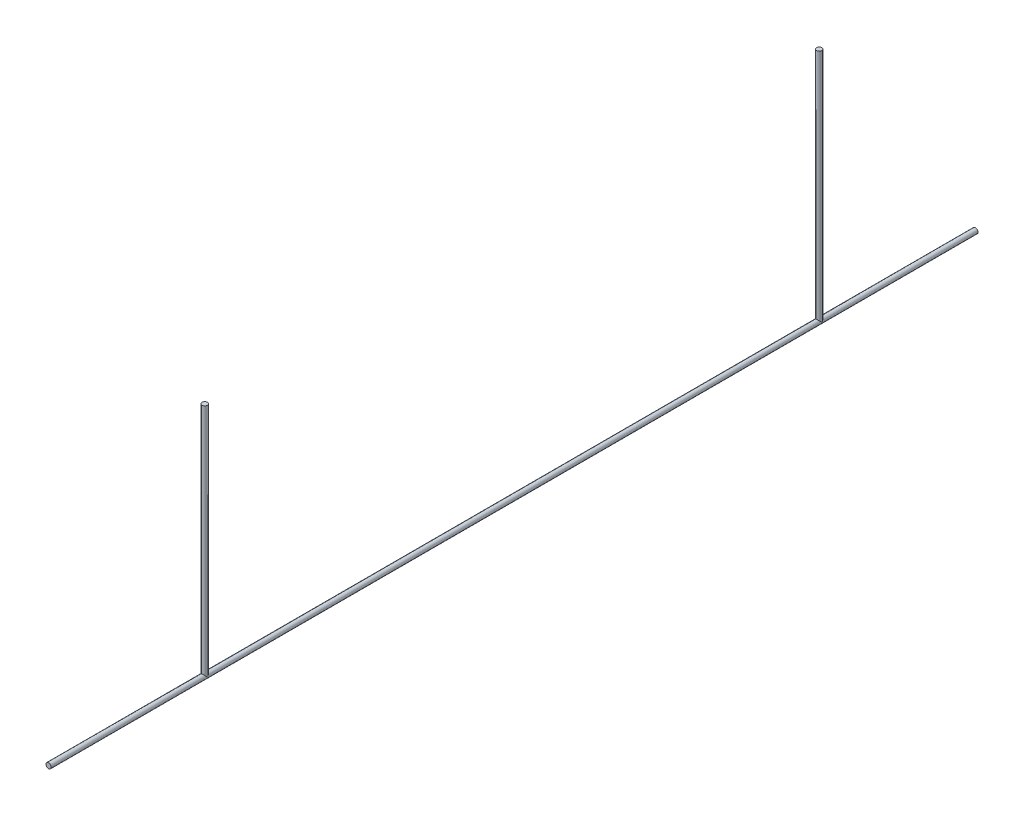
SolidWorks part; units mm, degrees
ref_plane "前视基准面" through (0, 0, 0) normal (0, 0, 1) x (1, 0, 0)
ref_plane "上视基准面" through (0, 0, 0) normal (0, 1, 0) x (1, 0, 0)
ref_plane "右视基准面" through (0, 0, 0) normal (1, 0, 0) x (0, 0, -1)
sketch "草图1" plane through (0, 0, 0) normal (0, 0, 1) x (1, 0, 0)
  circle A0 centre (0, 0) radius 5
extrude "凸台-拉伸1" add sketch "草图1" along normal blind 1780
sketch "草图2" plane through (0, 0, 0) normal (0, 1, 0) x (1, 0, 0)
  circle A0 centre (0, -300) radius 5
  circle A1 centre (0, -1480) radius 5
extrude "凸台-拉伸2" add sketch "草图2" along normal blind 452
